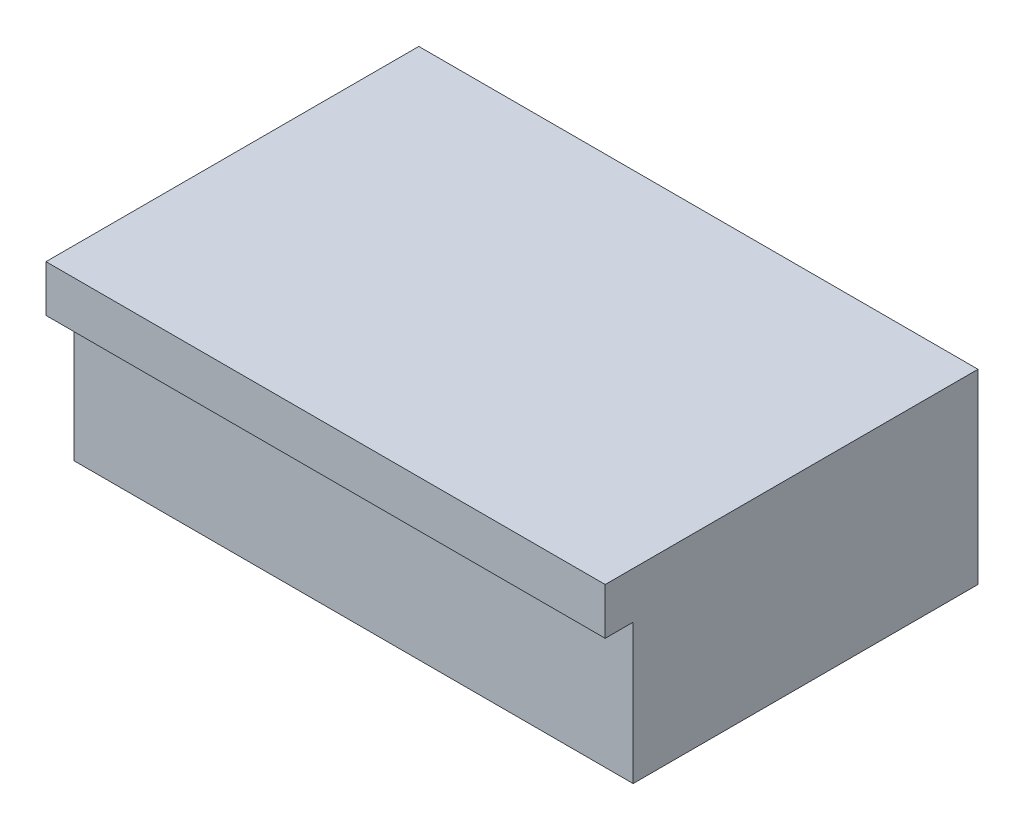
SolidWorks part; units mm, degrees
ref_plane "前视基准面" through (0, 0, 0) normal (0, 0, 1) x (1, 0, 0)
ref_plane "上视基准面" through (0, 0, 0) normal (0, 1, 0) x (1, 0, 0)
ref_plane "右视基准面" through (0, 0, 0) normal (1, 0, 0) x (0, 0, -1)
other "Configuration Table"
sketch "草图1" plane through (0, 0, 0) normal (0, 1, 0) x (1, 0, 0)
  line L1 (0, 0) -> (30, 0)
  line L2 (0, 0) -> (0, 20)
  line L3 (0, 20) -> (30, 20)
  line L4 (30, 0) -> (30, 20)
  dimension "D1" = 30
  dimension "D2" = 20
extrude "凸台-拉伸1" add sketch "草图1" along normal blind 10
sketch "草图2" plane through (0, 0, 0) normal (0, 0, 1) x (1, 0, 0)
  line L1 (0, 7.5) -> (30, 7.5)
  line L2 (0, 7.5) -> (0, 0)
  line L3 (0, 0) -> (30, 0)
  line L4 (30, 7.5) -> (30, 0)
  dimension "D1" = 7.5
extrude "切除-拉伸1" cut sketch "草图2" against normal blind 1.5
